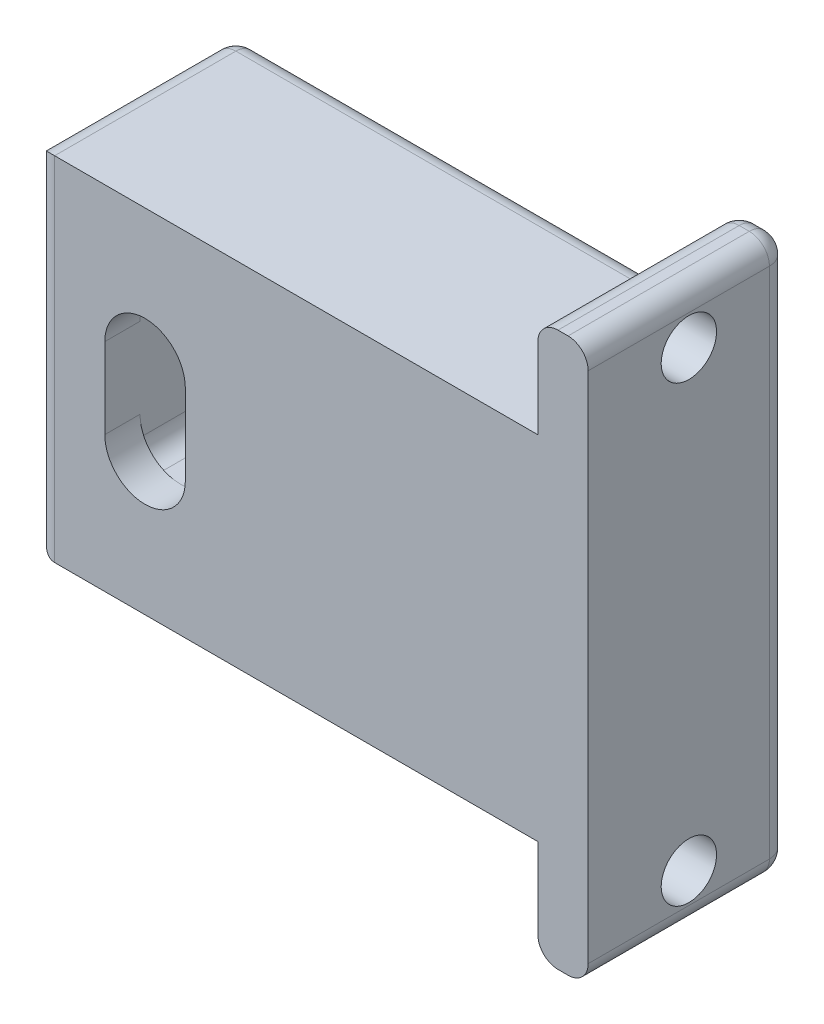
SolidWorks part; units mm, degrees
ref_plane "Front Plane" through (0, 0, 0) normal (0, 0, 1) x (1, 0, 0)
ref_plane "Top Plane" through (0, 0, 0) normal (0, 1, 0) x (1, 0, 0)
ref_plane "Right Plane" through (0, 0, 0) normal (1, 0, 0) x (0, 0, -1)
sketch "Sketch1" plane through (0, 0, 0) normal (1, 0, 0) x (0, 0, -1)
  line L1 (-20, 35) -> (0, 35)
  line L2 (-20, 35) -> (-20, 0)
  line L3 (-20, 0) -> (0, 0)
  line L4 (0, 35) -> (0, 0)
  dimension "D2" = 35
  dimension "D1" = 20
extrude "Boss-Extrude1" add sketch "Sketch1" along normal blind 50
sketch "Sketch2" plane through (50, 0, 0) normal (1, 0, 0) x (0, 0, -1)
  line L0 (0, 35) -> (-20, 35) construction
  line L1 (-20, 45) -> (0, 45)
  line L2 (-20, 45) -> (-20, -10)
  line L3 (-20, -10) -> (0, -10)
  line L4 (0, 45) -> (0, -10)
  line L5 (0, 0) -> (0, 35) construction
  line L7 (-20, 35) -> (-20, 0) construction
  line L8 (-20, 0) -> (0, 0) construction
  dimension "D1" = 10
  dimension "D2" = 0
  dimension "D3" = 10
  dimension "D4" = 0
extrude "Boss-Extrude2" add sketch "Sketch2" along normal blind 5
sketch "Sketch3" plane through (0, 0, 0) normal (0, 0, -1) x (-1, 0, 0)
  line L0 (0, 0) -> (0, 35) construction
  line L1 (-33.9808, 25.5) -> (-6.9808, 25.5)
  line L2 (-33.9808, 25.5) -> (-33.9808, 9.5)
  line L3 (-33.9808, 9.5) -> (-6.9808, 9.5)
  line L4 (-6.9808, 25.5) -> (-6.9808, 9.5)
  point P6 (0, 17.5)
  point P7 (-6.9808, 17.5)
  dimension "D1" = 27
  dimension "D2" = 16
extrude "Cut-Extrude1" cut sketch "Sketch3" against normal blind 16.5
sketch "Sketch4" plane through (0, 0, 16.5) normal (0, 0, -1) x (-1, 0, 0)
  line L0 (-10.9808, 21.5) -> (-10.9808, 13.5) construction
  line L1 (-6.9808, 21.5) -> (-6.9808, 13.5)
  line L2 (-14.9808, 21.5) -> (-14.9808, 13.5)
  line L3 (-6.9808, 25.5) -> (-33.9808, 25.5) construction
  line L4 (-33.9808, 9.5) -> (-6.9808, 9.5) construction
  line L6 (-6.9808, 9.5) -> (-6.9808, 25.5) construction
  arc A0 (-6.9808, 21.5) -> (-14.9808, 21.5) centre (-10.9808, 21.5) ccw
  arc A1 (-14.9808, 13.5) -> (-6.9808, 13.5) centre (-10.9808, 13.5) ccw
  point P2 (-10.9808, 17.5)
  dimension "D1" = 8
extrude "Cut-Extrude2" cut sketch "Sketch4" against normal blind 16.5
sketch "Sketch5" plane through (50, 0, 0) normal (-1, 0, 0) x (0, 0, 1)
  line L0 (20, 0) -> (0, 0) construction
  line L1 (0, 35) -> (0, 45) construction
  line L2 (0, -10) -> (0, 0) construction
  circle A0 centre (10, 40) radius 2.75
  circle A1 centre (10, -5) radius 2.75
  point P6 (10, 0)
  point P9 (0, 40)
  point P12 (0, -5)
  dimension "D1" = 5.5
extrude "Cut-Extrude3" cut sketch "Sketch5" against normal through all
fillet "Fillet1" radius 2 23 edges at (0, 0, 10) (0, 17.5, 0) (0, 35, 10) (0, 17.5, 20) (33.9808, 9.5, 8.25) (33.9808, 25.5, 8.25) (6.9808, 25.5, 8.25) (6.9808, 9.5, 8.25) (55, -10, 10) (50, -10, 10) (50, 45, 10) (55, 45, 10) (52.5, -10, 0) (50, -5, 0) (25, 0, 0) (55, 17.5, 0) (52.5, 45, 0) (50, 40, 0) (25, 35, 0) (33.9808, 17.5, 0) (20.4808, 9.5, 0) (20.4808, 25.5, 0) (6.9808, 17.5, 0)
